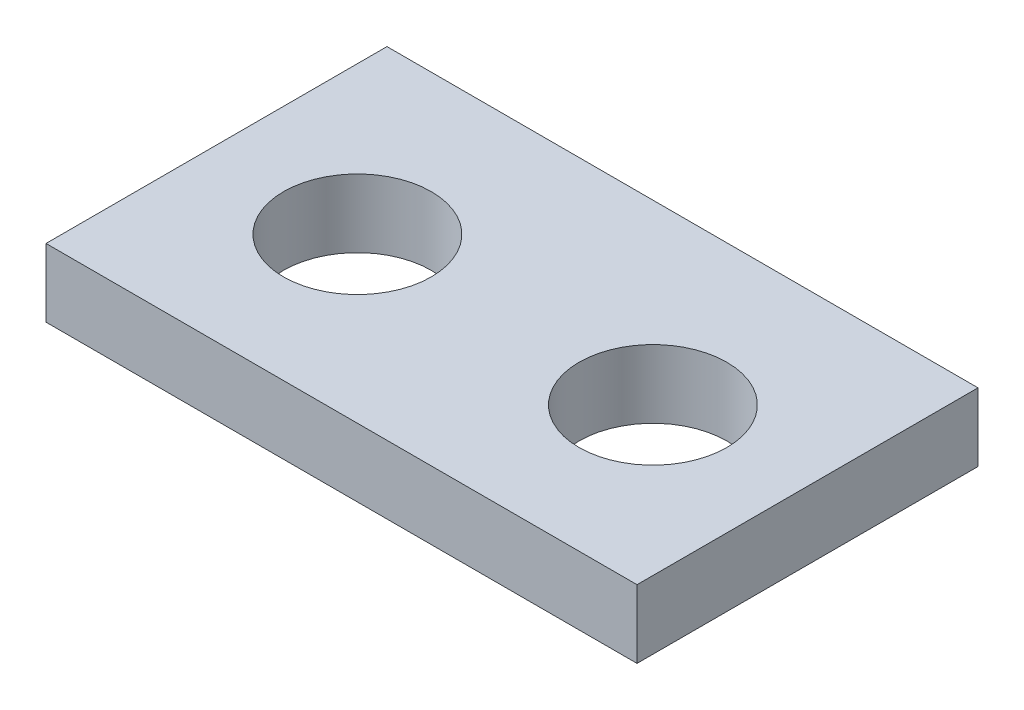
SolidWorks part; units mm, degrees
material "POM"
ref_plane "Front Plane" through (0, 0, 0) normal (0, 0, 1) x (1, 0, 0)
ref_plane "Top Plane" through (0, 0, 0) normal (0, 1, 0) x (1, 0, 0)
ref_plane "Right Plane" through (0, 0, 0) normal (1, 0, 0) x (0, 0, -1)
sketch "Sketch1" plane through (0, 0, 0) normal (0, 1, 0) x (1, 0, 0)
  line L1 (0, 0) -> (26, 0)
  line L2 (0, 0) -> (0, 15)
  line L3 (0, 15) -> (26, 15)
  line L4 (26, 0) -> (26, 15)
  circle A0 centre (6.5, 7.2) radius 3.25
  circle A1 centre (19.5, 7.2) radius 3.25
  dimension "D3" = 6.5
  dimension "D4" = 6.5
  dimension "D5" = 6.5
  dimension "D6" = 7.2
  dimension "D1" = 26
  dimension "D2" = 15
extrude "Boss-Extrude1" add sketch "Sketch1" against normal blind 3
